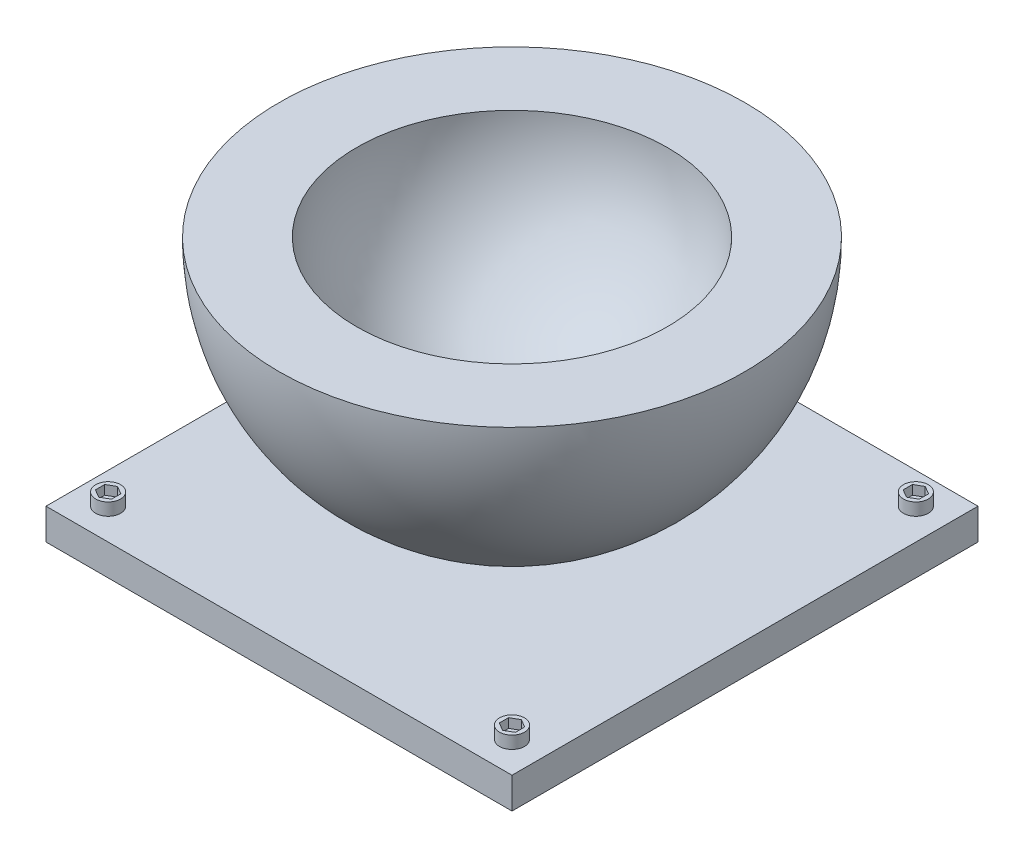
SolidWorks part; units mm, degrees
ref_plane "Front Plane" through (0, 0, 0) normal (0, 0, 1) x (1, 0, 0)
ref_plane "Top Plane" through (0, 0, 0) normal (0, 1, 0) x (1, 0, 0)
ref_plane "Right Plane" through (0, 0, 0) normal (1, 0, 0) x (0, 0, -1)
sketch "Sketch1" plane through (0, 0, 0) normal (0, 1, 0) x (1, 0, 0)
  line L0 (0, 37.5) -> (0, -37.5)
  line L1 (0, 18.6141) -> (0, -56.3859) construction
  arc A0 (0, 37.5) -> (0, -37.5) centre (0, 0) ccw
  arc A1 (0, -25) -> (0, 25) centre (0, 0) cw
  dimension "D2" = 25
  dimension "D1" = 75
revolve "Revolve3" add sketch "Sketch1" angle 180 about L1
ref_plane "Plane1" through (0, -37.5, 0) normal (0, -1, 0) x (-1, 0, 0)
sketch "Sketch2" plane through (0, -37.5, 0) normal (0, -1, 0) x (-1, 0, 0)
  line L1 (-37.5, 37.5) -> (37.5, 37.5)
  line L2 (-37.5, 37.5) -> (-37.5, -37.5)
  line L3 (-37.5, -37.5) -> (37.5, -37.5)
  line L4 (37.5, 37.5) -> (37.5, -37.5)
  line L5 (-37.5, 37.5) -> (37.5, -37.5) construction
  line L6 (-37.5, -37.5) -> (37.5, 37.5) construction
  point P0 (0, 0)
  dimension "D1" = 75
extrude "Boss-Extrude1" add sketch "Sketch2" along normal blind 5 separate body
sketch "Sketch3" plane through (0, -37.5, 0) normal (0, 1, 0) x (1, 0, 0)
  line L1 (37.5, -37.5) -> (32.5, -37.5) construction
  line L2 (37.5, -37.5) -> (37.5, -32.5) construction
  line L3 (37.5, -32.5) -> (32.5, -32.5) construction
  line L4 (32.5, -37.5) -> (32.5, -32.5) construction
  line L5 (37.5, -37.5) -> (32.5, -32.5) construction
  line L6 (37.5, -32.5) -> (32.5, -37.5) construction
  circle A0 centre (32.5, -32.5) radius 1.5
  point P2 (35, -35)
  point P7 (0, 0)
  point P8 (0, 0)
  dimension "D2" = 3
  dimension "D1" = 5
extrude "Cut-Extrude1" cut sketch "Sketch3" against normal up to surface (5 mm away) up to face at (0, -42.5, 0)
sketch "Sketch4" plane through (0, -37.5, 0) normal (0, 1, 0) x (1, 0, 0)
  circle A0 centre (32.5, -32.5) radius 2
  circle A1 centre (32.5, -32.5) radius 1.5 construction
  point P2 (0, 0)
  dimension "D1" = 4
extrude "Boss-Extrude2" add sketch "Sketch4" along normal blind 2
sketch "Sketch5" plane through (0, -35.5, 0) normal (0, 1, 0) x (1, 0, 0)
  line L1 (31.201, -31.75) -> (31.201, -33.25)
  line L2 (31.201, -33.25) -> (32.5, -34)
  line L3 (32.5, -34) -> (33.799, -33.25)
  line L4 (33.799, -33.25) -> (33.799, -31.75)
  line L5 (33.799, -31.75) -> (32.5, -31)
  line L6 (32.5, -31) -> (31.201, -31.75)
  circle A0 centre (32.5, -32.5) radius 1.299 construction
  circle A1 centre (32.5, -32.5) radius 2 construction
  point P1 (0, 0)
  point P10 (0, 0)
  point P12 (0, 0)
  dimension "D1" = 1.5
extrude "Cut-Extrude2" cut sketch "Sketch5" against normal blind 1.5
sketch "Sketch6" plane through (0, -42.5, 0) normal (0, -1, 0) x (1, 0, 0)
  circle A0 centre (32.5, 32.5) radius 1.5
  circle A1 centre (32.5, 32.5) radius 1.5 construction
extrude "Boss-Extrude3" add sketch "Sketch6" against normal up to next
mirror "Mirror1" about plane through (0, 0, 0) normal (0, 0, 1) of "Boss-Extrude3", "Cut-Extrude2", "Boss-Extrude2", "Cut-Extrude1"
mirror "Mirror2" about plane through (0, 0, 0) normal (1, 0, 0) of "Mirror1", "Boss-Extrude2", "Cut-Extrude2"
